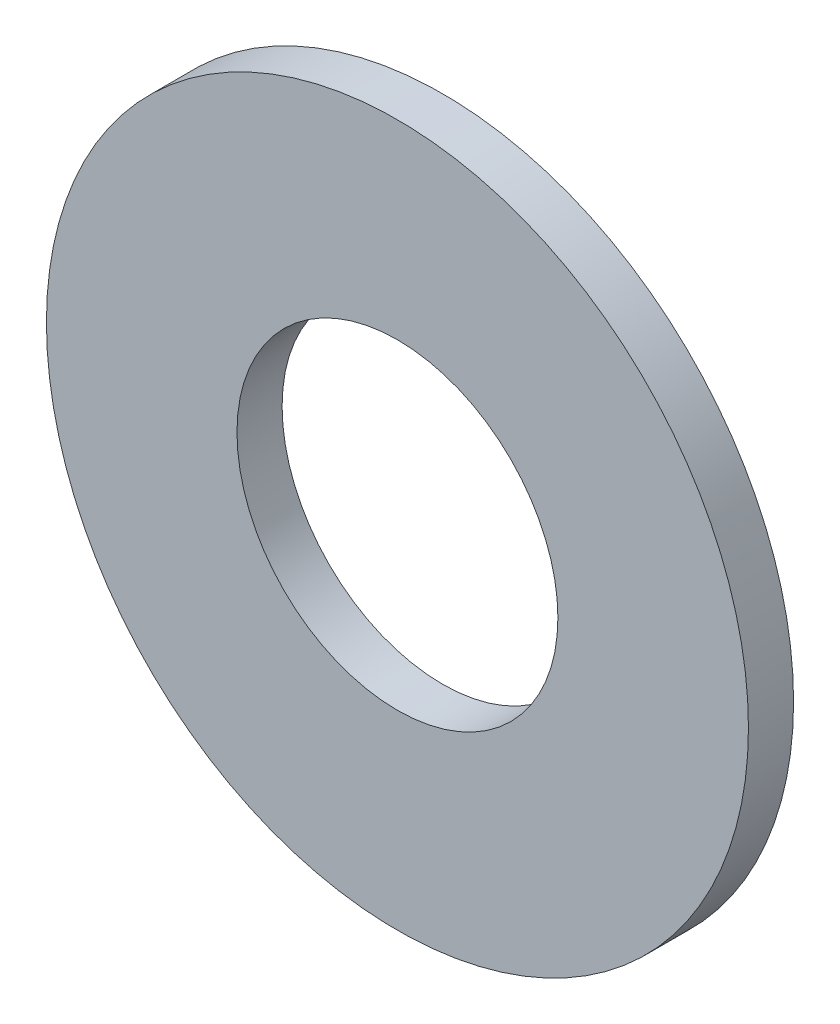
SolidWorks part; units mm, degrees
material "Chrome Stainless Steel"
ref_plane "Front Plane" through (0, 0, 0) normal (0, 0, 1) x (1, 0, 0)
ref_plane "Top Plane" through (0, 0, 0) normal (0, 1, 0) x (1, 0, 0)
ref_plane "Right Plane" through (0, 0, 0) normal (1, 0, 0) x (0, 0, -1)
sketch "Sketch1" plane through (0, 0, 0) normal (0, 0, 1) x (1, 0, 0)
  circle A0 centre (0, 0) radius 3.5
  circle A1 centre (0, 0) radius 1.6
  dimension "D1" = 3.2
  dimension "D2" = 7
extrude "Boss-Extrude1" add sketch "Sketch1" along normal blind 0.45
